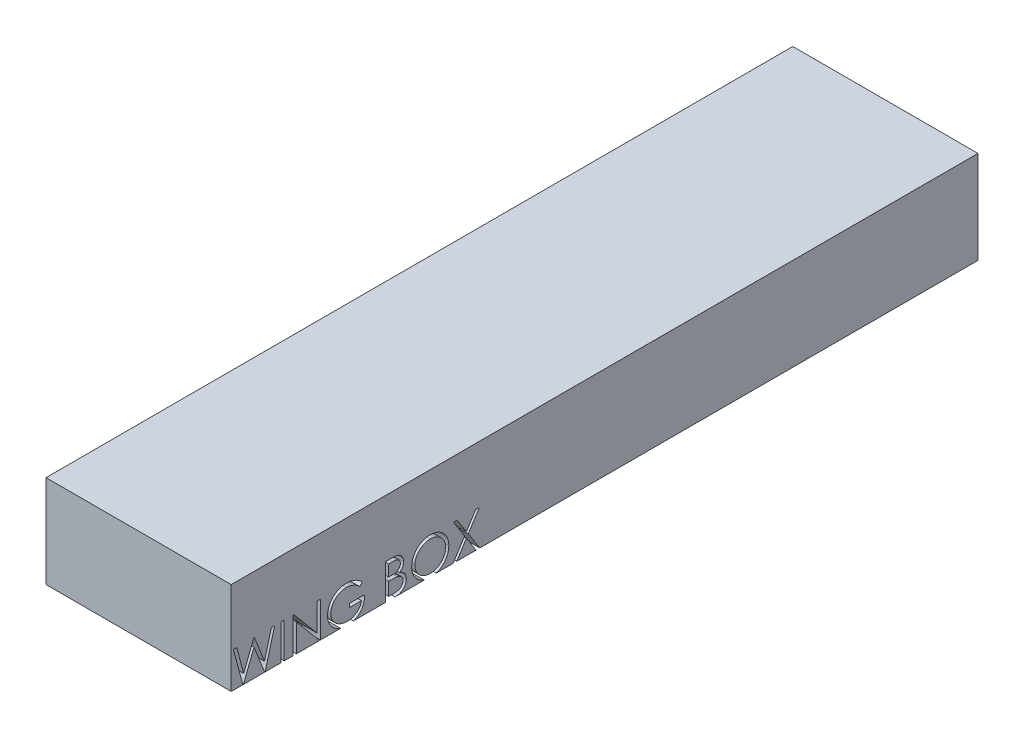
SolidWorks part; units mm, degrees
ref_plane "Front Plane" through (0, 0, 0) normal (0, 0, 1) x (1, 0, 0)
ref_plane "Top Plane" through (0, 0, 0) normal (0, 1, 0) x (1, 0, 0)
ref_plane "Right Plane" through (0, 0, 0) normal (1, 0, 0) x (0, 0, -1)
sketch "Sketch1" plane through (0, 0, 0) normal (1, 0, 0) x (0, 0, -1)
  line L1 (-403.2, 50) -> (0, 50)
  line L2 (-403.2, 50) -> (-403.2, 0)
  line L3 (-403.2, 0) -> (0, 0)
  line L4 (0, 50) -> (0, 0)
  point P4 (0, 0)
  point P5 (0, 0)
  dimension "D1" = 50
  dimension "D2" = 403.2
extrude "Boss-Extrude1" add sketch "Sketch1" along normal mid plane 100
sketch "Sketch2" plane through (50, 0, 0) normal (1, 0, 0) x (0, 0, -1)
  line L0 (-403.2, 50) -> (-403.2, 0) construction
  line L1 (-403.2, 0) -> (0, 0) construction
  text T0 "WING BOX\r\n" font "Century Gothic" height in points 72
  point P1 (-403.2, 0)
extrude "Cut-Extrude1" cut sketch "Sketch2" against normal blind 10
